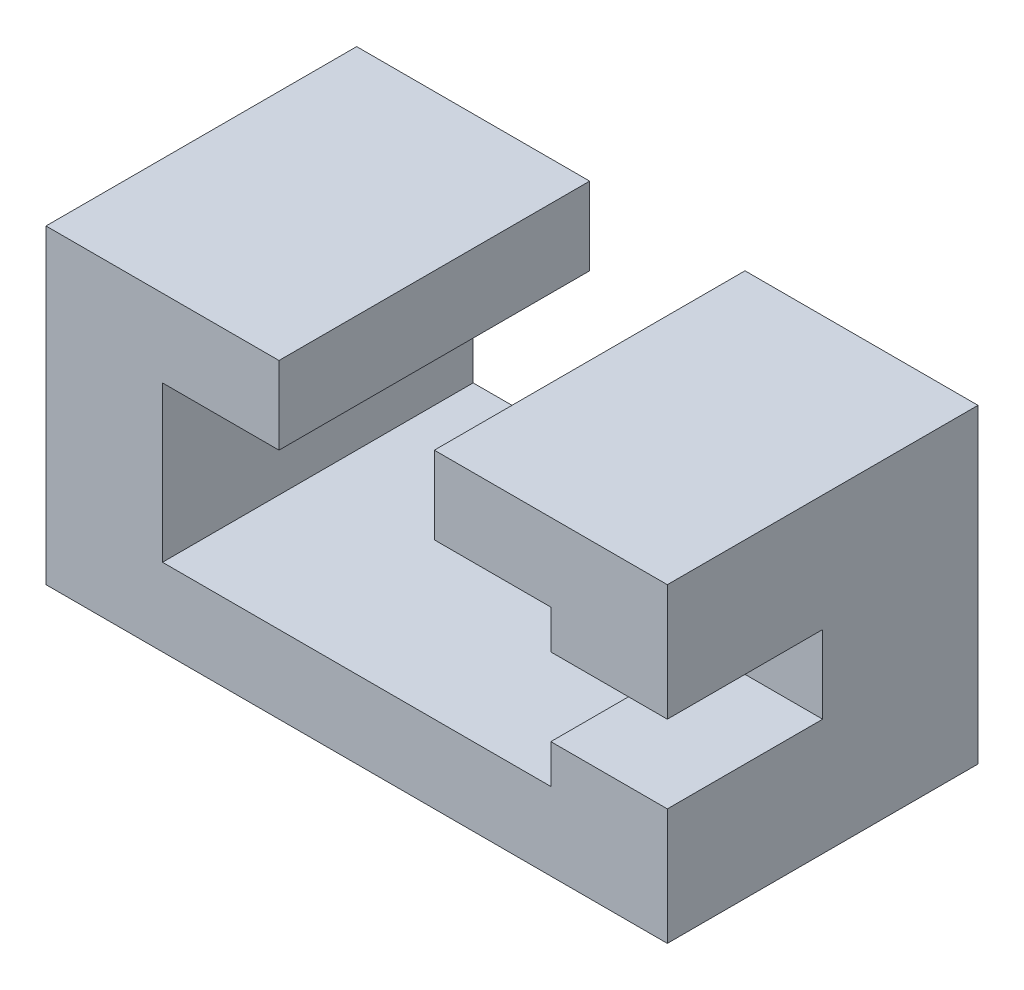
SolidWorks part; units mm, degrees
ref_plane "Front Plane" through (0, 0, 0) normal (0, 0, 1) x (1, 0, 0)
ref_plane "Top Plane" through (0, 0, 0) normal (0, 1, 0) x (1, 0, 0)
ref_plane "Right Plane" through (0, 0, 0) normal (1, 0, 0) x (0, 0, -1)
sketch "Sketch1" plane through (0, 0, 0) normal (0, 0, 1) x (1, 0, 0)
  line L0 (0, 40) -> (0, 0)
  line L1 (0, 0) -> (80, 0)
  line L2 (80, 0) -> (80, 40)
  line L3 (80, 40) -> (50, 40)
  line L4 (50, 40) -> (50, 30)
  line L5 (50, 30) -> (65, 30)
  line L6 (65, 30) -> (65, 10)
  line L7 (65, 10) -> (15, 10)
  line L8 (15, 10) -> (15, 30)
  line L9 (15, 30) -> (30, 30)
  line L10 (30, 30) -> (30, 40)
  line L11 (30, 40) -> (0, 40)
  point P12 (54.4765, 46.3753)
  point P13 (0, 0)
  point P14 (0, 0)
  dimension "D1" = 30
  dimension "D3" = 10
  dimension "D4" = 20
  dimension "D5" = 15
  dimension "D6" = 40
  dimension "D7" = 50
  dimension "D8" = 80
extrude "Boss-Extrude1" add sketch "Sketch1" along normal blind 40
sketch "Sketch2" plane through (80, 0, 0) normal (1, 0, 0) x (0, 0, -1)
  line L0 (-40, 25) -> (-20, 25)
  line L1 (-40, 0) -> (-40, 40) construction
  line L2 (-20, 25) -> (-20, 15)
  line L3 (-20, 15) -> (-40, 15)
  line L4 (-40, 25) -> (-40, 15)
  line L5 (-40, 40) -> (0, 40) construction
  dimension "D1" = 20
  dimension "D2" = 10
  dimension "D3" = 15
extrude "Cut-Extrude1" cut sketch "Sketch2" against normal up to next contours L4 L3 L2 L0
